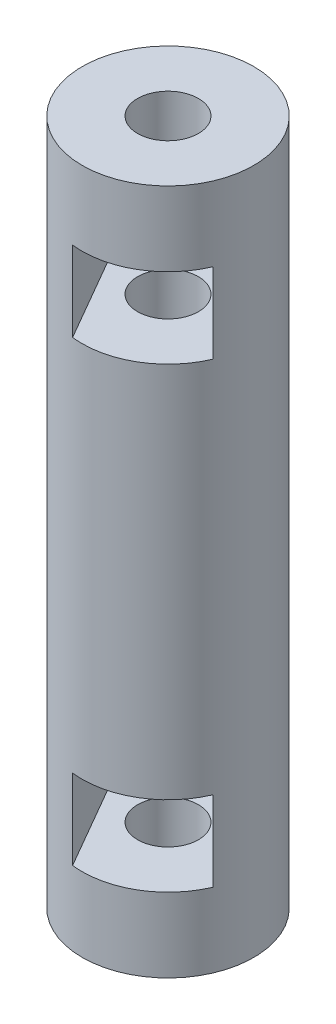
SolidWorks part; units mm, degrees
ref_plane "Front Plane" through (0, 0, 0) normal (0, 0, 1) x (1, 0, 0)
ref_plane "Top Plane" through (0, 0, 0) normal (0, 1, 0) x (1, 0, 0)
ref_plane "Right Plane" through (0, 0, 0) normal (1, 0, 0) x (0, 0, -1)
sketch "Sketch1" plane through (0, 0, 0) normal (0, 1, 0) x (1, 0, 0)
  circle A0 centre (0, 0) radius 9.525
  dimension "D1" = 19.05
extrude "Boss-Extrude1" add sketch "Sketch1" along normal mid plane 76.2
ref_plane "Plane1" through (0, -25.4, 0) normal (0, -1, 0) x (-1, 0, 0)
sketch "Sketch2" plane through (0, -25.4, 0) normal (0, -1, 0) x (-1, 0, 0)
  line L0 (-9.525, 0) -> (9.525, 0)
  line L1 (3.2996, -5.715) -> (6.5991, 0)
  line L2 (6.5991, 0) -> (3.2996, 5.715)
  line L3 (3.2996, 5.715) -> (-3.2996, 5.715)
  line L4 (-3.2996, 5.715) -> (-6.5991, 0)
  line L5 (-6.5991, 0) -> (-3.2996, -5.715)
  line L6 (-3.2996, -5.715) -> (3.2996, -5.715)
  line L7 (-6.5991, 0) -> (-8.7593, -3.7416)
  line L8 (3.2996, -5.715) -> (1.1393, -9.4566)
  circle A0 centre (0, 0) radius 5.715 construction
  circle A1 centre (0, 0) radius 9.525 construction
  arc A2 (1.1393, -9.4566) -> (-8.7593, -3.7416) centre (0, 0) cw
  point P17 (0, 0)
  point P18 (0, 0)
  dimension "D1" = 11.43
extrude "Cut-Extrude1" cut sketch "Sketch2" against normal mid plane 8.89 contours L3 L4 L0 L2 | L5 L6 L1 L0 | A2 L8 L6 L5 L7
mirror "Mirror1" about plane through (0, 0, 0) normal (0, 1, 0) of "Cut-Extrude1"
sketch "Sketch3" plane through (0, 38.1, 0) normal (0, 1, 0) x (1, 0, 0)
  circle A0 centre (0, 0) radius 3.3782
  dimension "D1" = 6.7564
extrude "Cut-Extrude2" cut sketch "Sketch3" against normal through all
